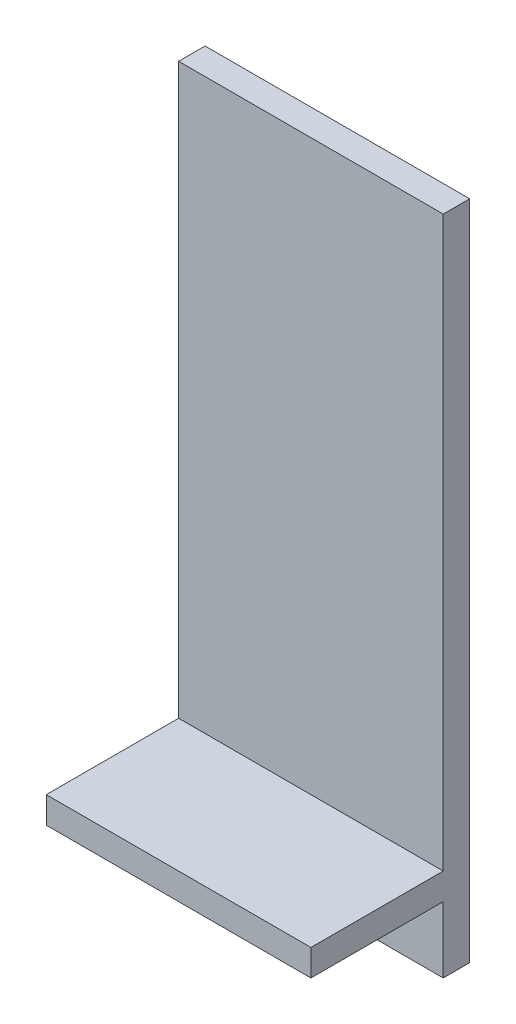
SolidWorks part; units mm, degrees
ref_plane "Alzado" through (0, 0, 0) normal (0, 0, 1) x (1, 0, 0)
ref_plane "Planta" through (0, 0, 0) normal (0, 1, 0) x (1, 0, 0)
ref_plane "Vista lateral" through (0, 0, 0) normal (1, 0, 0) x (0, 0, -1)
sketch "Croquis1" plane through (0, 0, 0) normal (0, 1, 0) x (1, 0, 0)
  line L0 (0, 0) -> (20, 0)
  line L1 (20, 0) -> (20, 2)
  line L2 (20, 2) -> (0, 2)
  line L3 (0, 2) -> (0, 0)
  dimension "D1" = 20
  dimension "D2" = 2
extrude "Saliente-Extruir1" add sketch "Croquis1" along normal blind 50
sketch "Croquis2" plane through (0, 0, 0) normal (0, 0, 1) x (1, 0, 0)
  line L0 (8, 0) -> (8, 5)
  line L1 (0, 0) -> (20, 0) construction
  line L2 (8, 5) -> (12, 5)
  line L3 (12, 5) -> (12, 0)
  line L4 (0, 50) -> (0, 0) construction
  line L5 (12, 0) -> (8, 0)
  dimension "D1" = 5
  dimension "D2" = 4
  dimension "D3" = 8
extrude "Saliente-Extruir2" add sketch "Croquis2" along normal blind 4
sketch "Croquis3" plane through (0, 0, 0) normal (0, 0, 1) x (1, 0, 0)
  line L0 (12, 5) -> (20, 5)
  line L1 (20, 50) -> (20, 0) construction
  line L2 (20, 5) -> (20, 7)
  line L3 (20, 7) -> (0, 7)
  line L4 (0, 50) -> (0, 0) construction
  line L5 (0, 7) -> (0, 5)
  line L6 (0, 5) -> (12, 5)
  dimension "D1" = 2
extrude "Saliente-Extruir3" add sketch "Croquis3" along normal blind 10
sketch "Croquis4" plane through (0, 0, 0) normal (0, 0, 1) x (1, 0, 0)
